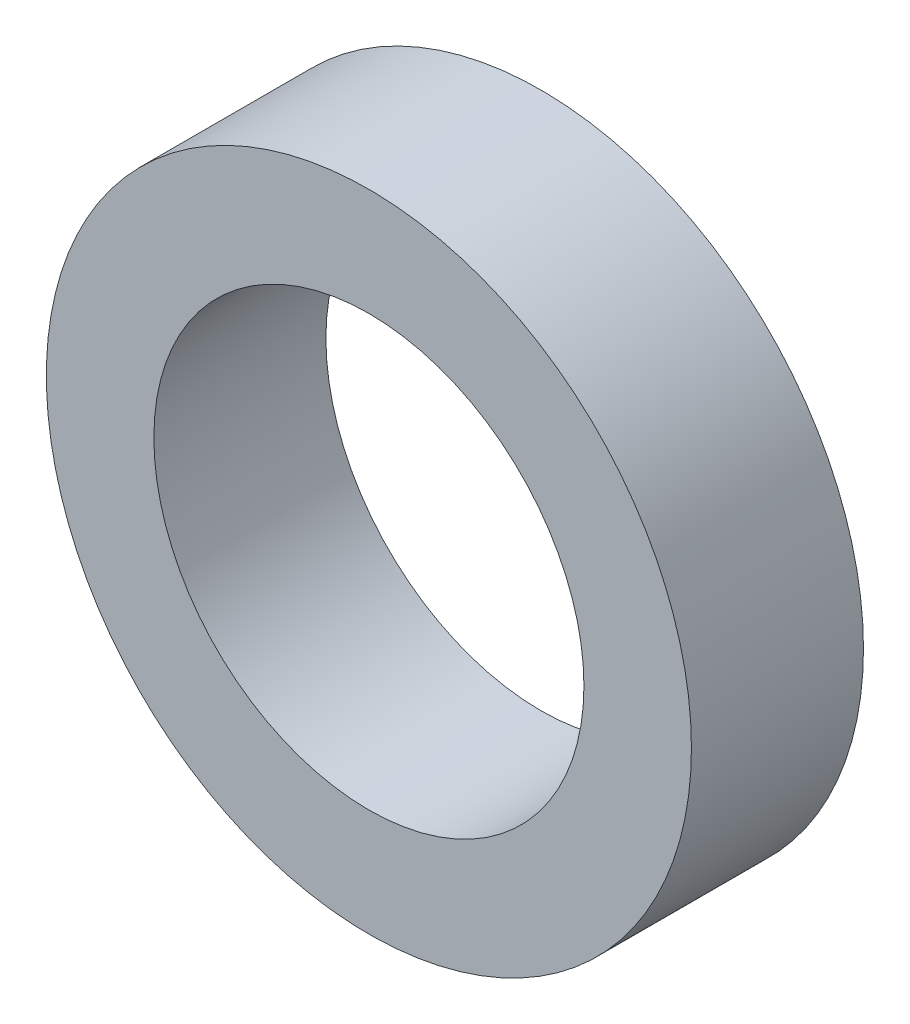
SolidWorks part; units mm, degrees
ref_plane "前视基准面" through (0, 0, 0) normal (0, 0, 1) x (1, 0, 0)
ref_plane "上视基准面" through (0, 0, 0) normal (0, 1, 0) x (1, 0, 0)
ref_plane "右视基准面" through (0, 0, 0) normal (1, 0, 0) x (0, 0, -1)
sketch "草图1" plane through (0, 0, 0) normal (0, 0, 1) x (1, 0, 0)
  circle A0 centre (0, 0) radius 5
  circle A1 centre (0, 0) radius 7.5
  dimension "D1" = 10
  dimension "D2" = 15
extrude "凸台-拉伸1" add sketch "草图1" along normal blind 4
